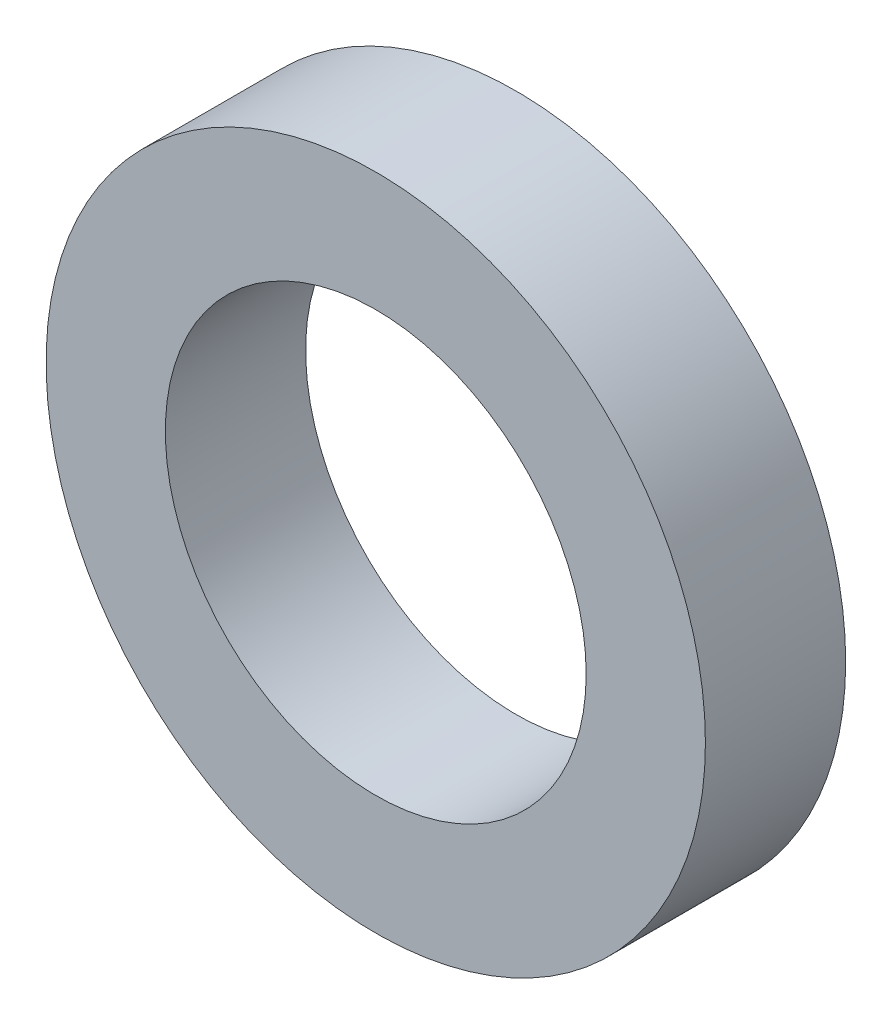
SolidWorks part; units mm, degrees
ref_plane "Piano frontale" through (0, 0, 0) normal (0, 0, 1) x (1, 0, 0)
ref_plane "Piano superiore" through (0, 0, 0) normal (0, 1, 0) x (1, 0, 0)
ref_plane "Piano destro" through (0, 0, 0) normal (1, 0, 0) x (0, 0, -1)
sketch "Schizzo1" plane through (0, 0, 0) normal (0, 0, 1) x (1, 0, 0)
  circle A0 centre (0, 0) radius 1.5
  circle A1 centre (0, 0) radius 2.35
  dimension "D1" = 3
  dimension "D2" = 4.7
extrude "Estrusione-Estrusione1" add sketch "Schizzo1" along normal blind 1
